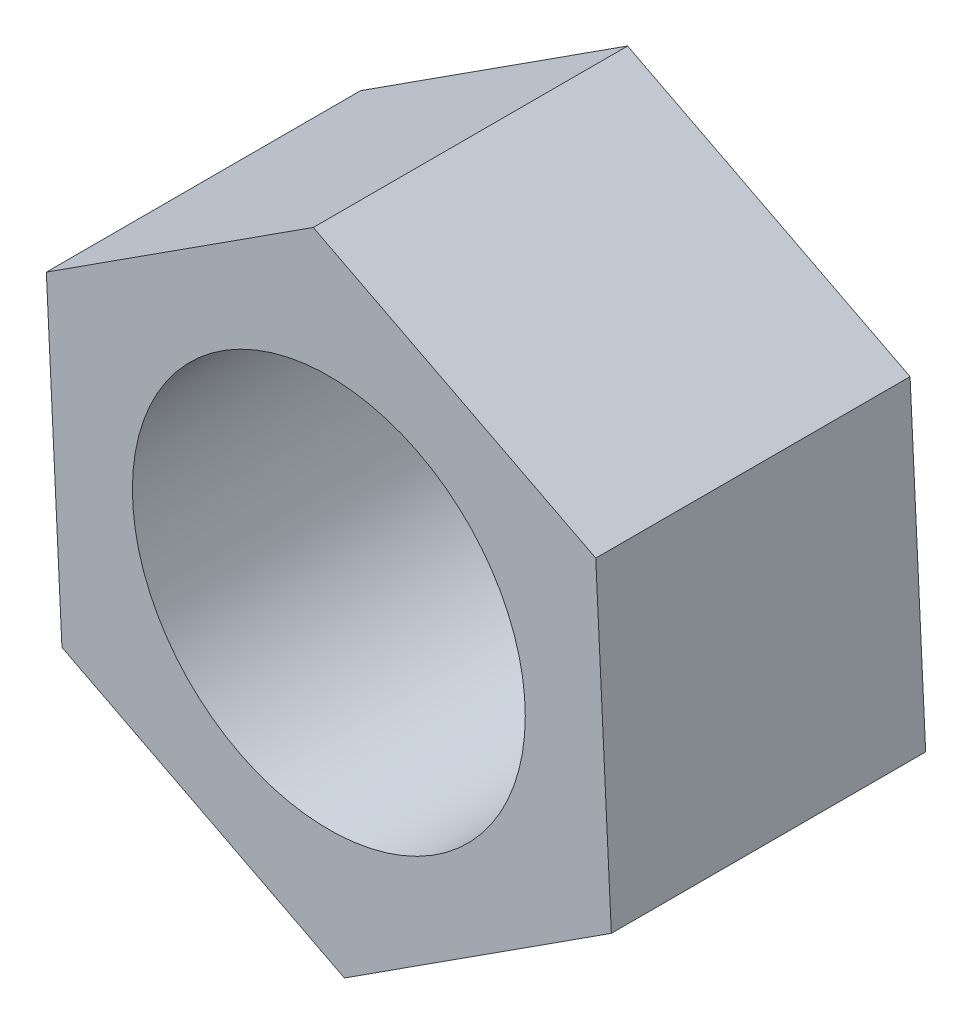
SolidWorks part; units mm, degrees
ref_plane "Front Plane" through (0, 0, 0) normal (0, 0, 1) x (1, 0, 0)
ref_plane "Top Plane" through (0, 0, 0) normal (0, 1, 0) x (1, 0, 0)
ref_plane "Right Plane" through (0, 0, 0) normal (1, 0, 0) x (0, 0, -1)
sketch "Sketch1" plane through (0, 0, 0) normal (0, 0, 1) x (1, 0, 0)
  line L1 (-0.1983, 4.0366) -> (-3.5949, 1.8465)
  line L2 (-3.5949, 1.8465) -> (-3.3966, -2.19)
  line L3 (-3.3966, -2.19) -> (0.1983, -4.0366)
  line L4 (0.1983, -4.0366) -> (3.5949, -1.8465)
  line L5 (3.5949, -1.8465) -> (3.3966, 2.19)
  line L6 (3.3966, 2.19) -> (-0.1983, 4.0366)
  circle A0 centre (0, 0) radius 3.5 construction
  circle A1 centre (0, 0) radius 2.5
  dimension "D1" = 7
  dimension "D2" = 5
extrude "Boss-Extrude1" add sketch "Sketch1" along normal blind 4
